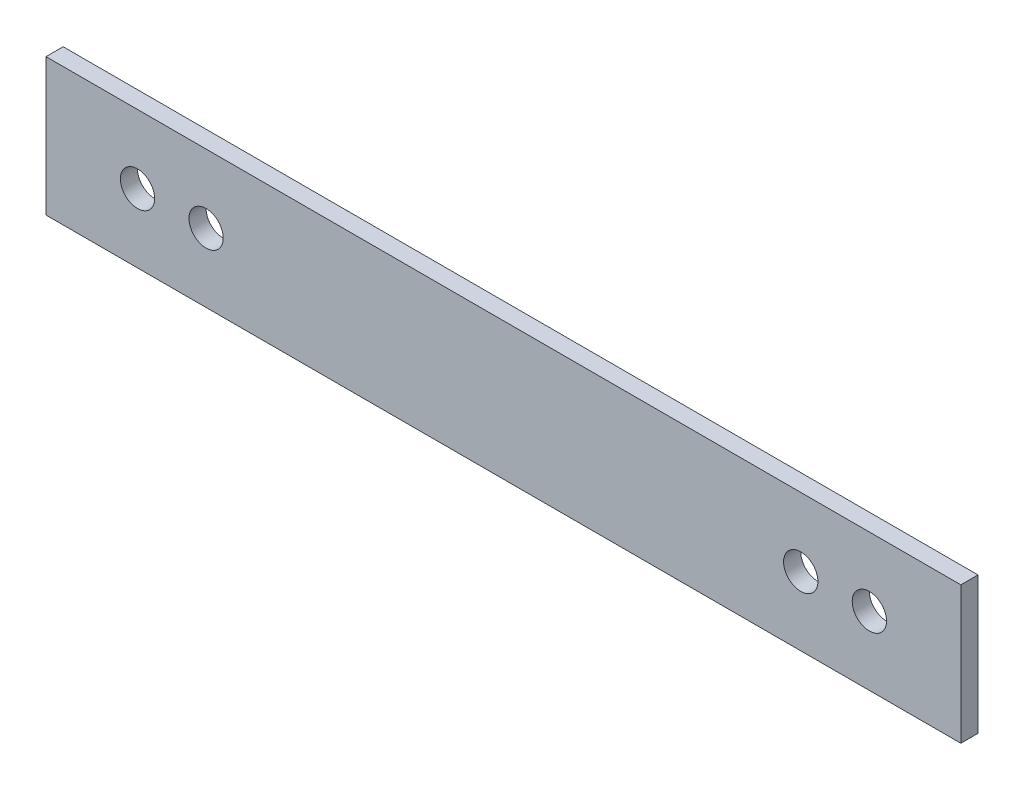
SolidWorks part; units mm, degrees
ref_plane "Front Plane" through (0, 0, 0) normal (0, 0, 1) x (1, 0, 0)
ref_plane "Top Plane" through (0, 0, 0) normal (0, 1, 0) x (1, 0, 0)
ref_plane "Right Plane" through (0, 0, 0) normal (1, 0, 0) x (0, 0, -1)
sketch "Sketch1" plane through (0, 0, 0) normal (0, 0, 1) x (1, 0, 0)
  line L1 (0, 0) -> (254, 0)
  line L2 (0, 0) -> (0, 38.1)
  line L3 (0, 38.1) -> (254, 38.1)
  line L4 (254, 0) -> (254, 38.1)
  circle A0 centre (209.55, 19.05) radius 4.7625
  circle A1 centre (228.6, 19.05) radius 4.7625
  circle A2 centre (25.4, 19.05) radius 4.7625
  circle A3 centre (44.45, 19.05) radius 4.7625
  point P9 (254, 19.05)
  point P14 (0, 19.05)
  dimension "D5" = 9.525
  dimension "D6" = 9.525
  dimension "D1" = 38.1
  dimension "D2" = 254
  dimension "D3" = 19.05
  dimension "D4" = 25.4
  dimension "D7" = 19.05
  dimension "D8" = 25.4
extrude "Boss-Extrude1" add sketch "Sketch1" along normal blind 4.7625
